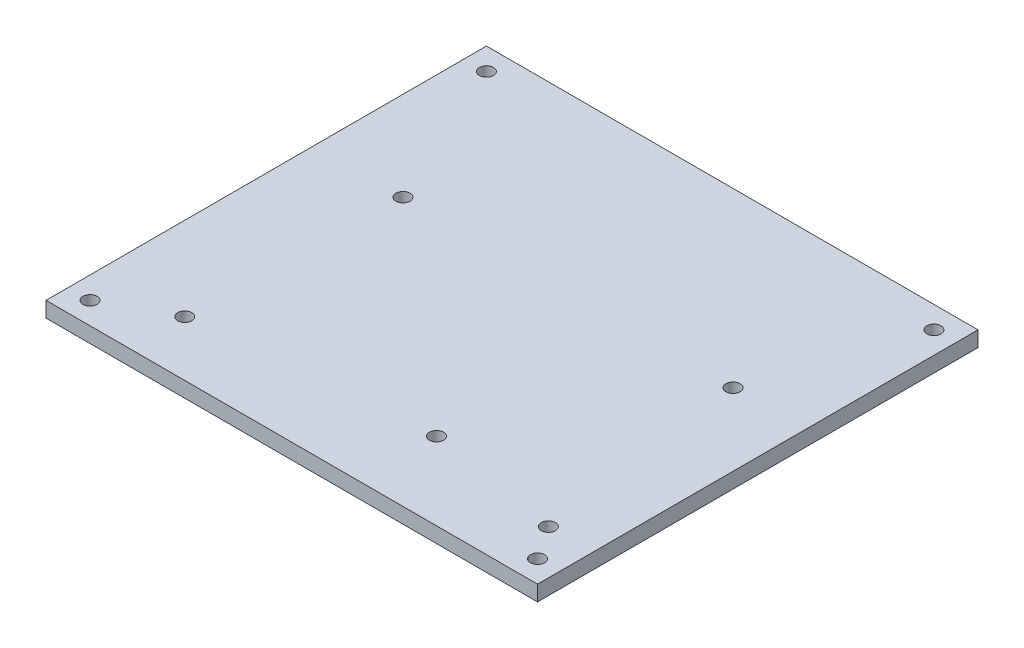
SolidWorks part; units mm, degrees
ref_plane "Front Plane" through (0, 0, 0) normal (0, 0, 1) x (1, 0, 0)
ref_plane "Top Plane" through (0, 0, 0) normal (0, 1, 0) x (1, 0, 0)
ref_plane "Right Plane" through (0, 0, 0) normal (1, 0, 0) x (0, 0, -1)
sketch "Sketch1" plane through (0, 0, 0) normal (0, 1, 0) x (1, 0, 0)
  line L0 (106.6, 5) -> (106.6, 10) construction
  line L1 (0, 0) -> (111.6, 0)
  line L2 (0, 0) -> (0, 100)
  line L3 (0, 100) -> (111.6, 100)
  line L4 (111.6, 0) -> (111.6, 100)
  line L9 (5, 10) -> (106.6, 10) construction
  line L10 (5, 10) -> (5, 63.34) construction
  line L11 (5, 63.34) -> (106.6, 63.34) construction
  line L12 (106.6, 10) -> (106.6, 63.34) construction
  line L13 (106.6, 10) -> (111.6, 10) construction
  line L14 (106.6, 95) -> (106.6, 100) construction
  line L15 (55.8, 100) -> (55.8, 0) construction
  circle A0 centre (20.24, 60.8) radius 1.6
  circle A1 centre (18.97, 12.54) radius 1.6
  circle A2 centre (71.04, 17.62) radius 1.6
  circle A3 centre (101.52, 12.54) radius 1.6
  circle A4 centre (95.17, 60.8) radius 1.6
  circle A5 centre (106.6, 5) radius 1.6
  circle A8 centre (106.6, 95) radius 1.6
  circle A9 centre (5, 5) radius 1.6
  circle A10 centre (5, 95) radius 1.6
  point P9 (55.8, 10)
  point P10 (55.8, 0)
  dimension "D9" = 3.2
  dimension "D1" = 15.24
  dimension "D2" = 50.8
  dimension "D3" = 13.97
  dimension "D4" = 2.54
  dimension "D5" = 66.04
  dimension "D6" = 96.52
  dimension "D7" = 101.6
  dimension "D8" = 90.17
  dimension "D10" = 100
  dimension "D11" = 5
  dimension "D12" = 10
  dimension "D13" = 53.34
  dimension "D14" = 7.62
extrude "Boss-Extrude1" add sketch "Sketch1" along normal blind 3.5
